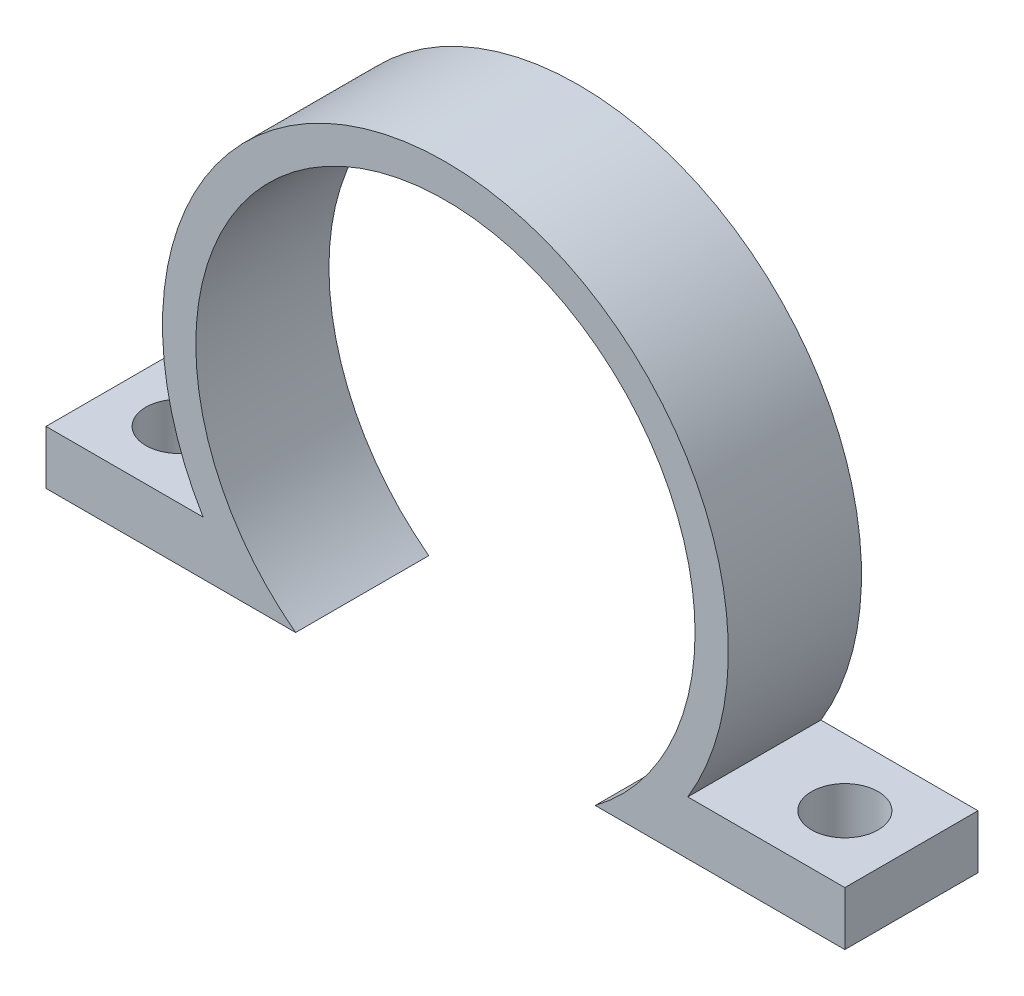
SolidWorks part; units mm, degrees
ref_plane "Front Plane" through (0, 0, 0) normal (0, 0, 1) x (1, 0, 0)
ref_plane "Top Plane" through (0, 0, 0) normal (0, 1, 0) x (1, 0, 0)
ref_plane "Right Plane" through (0, 0, 0) normal (1, 0, 0) x (0, 0, -1)
sketch "Sketch1" plane through (0, 0, 0) normal (0, 1, 0) x (1, 0, 0)
  line L0 (31.75, 3.175) -> (19.05, 3.175)
  line L1 (19.05, 3.175) -> (19.05, -6.985)
  line L2 (19.05, -6.985) -> (31.75, -6.985)
  line L3 (31.75, -6.985) -> (31.75, 3.175)
  line L4 (-19.05, 3.175) -> (-31.75, 3.175)
  line L5 (-31.75, 3.175) -> (-31.75, -6.985)
  line L6 (-31.75, -6.985) -> (-19.05, -6.985)
  line L7 (-19.05, -6.985) -> (-19.05, 3.175)
  line L8 (-19.05, 3.175) -> (19.05, 3.175)
  line L9 (19.05, -6.985) -> (-19.05, -6.985)
  line L10 (-25.4, 3.175) -> (-25.4, -1.905) construction
  line L11 (25.4, -1.905) -> (25.4, 3.175) construction
  circle A0 centre (-25.4, -1.905) radius 2.54
  circle A1 centre (25.4, -1.905) radius 2.54
  dimension "D4" = 5.08
  dimension "D5" = 5.08
  dimension "D1" = 10.16
  dimension "D2" = 5.08
  dimension "D3" = 5.08
extrude "Boss-Extrude1" add sketch "Sketch1" along normal blind 50.8 contours L9 L1 L8 L7 | L6 L7 L4 L5 A0 | L2 L3 L0 L1 A1
sketch "Sketch2" plane through (0, 0, 6.985) normal (0, 0, 1) x (1, 0, 0)
  line L0 (-31.75, 50.8) -> (-31.75, 0) construction
  line L1 (0, 6.35) -> (0, 10.16) construction
  line L3 (0, 10.16) -> (-11.43, 10.16) construction
  line L4 (-30.48, 10.16) -> (-30.48, 14.2584)
  line L5 (0, 0) -> (0, 8.7808) construction
  line L6 (0, 10.16) -> (11.43, 10.16) construction
  line L7 (0, 8.7808) -> (0, 25.4) construction
  line L8 (-11.43, 10.16) -> (-30.48, 10.16)
  line L9 (-18.4931, 14.2584) -> (-30.48, 14.2584)
  line L10 (11.43, 10.16) -> (30.48, 10.16)
  line L11 (18.4931, 14.2584) -> (30.48, 14.2584)
  line L12 (30.48, 14.2584) -> (30.48, 10.16)
  arc A1 (11.43, 10.16) -> (-11.43, 10.16) centre (0, 25.4) ccw
  arc A2 (18.4931, 14.2584) -> (-18.4931, 14.2584) centre (0, 25.4) ccw
  arc A4 (12.954, 8.128) -> (-12.954, 8.128) centre (0, 25.4) ccw construction
  point P1 (0, 0)
  point P10 (-31.75, 25.4)
  point P14 (21.59, 0)
  point P15 (-21.59, 0)
  dimension "D1" = 2.54
  dimension "D3" = 19.05
  dimension "D2" = 19.05
extrude "Cut-Extrude1" cut sketch "Sketch2" against normal through all
